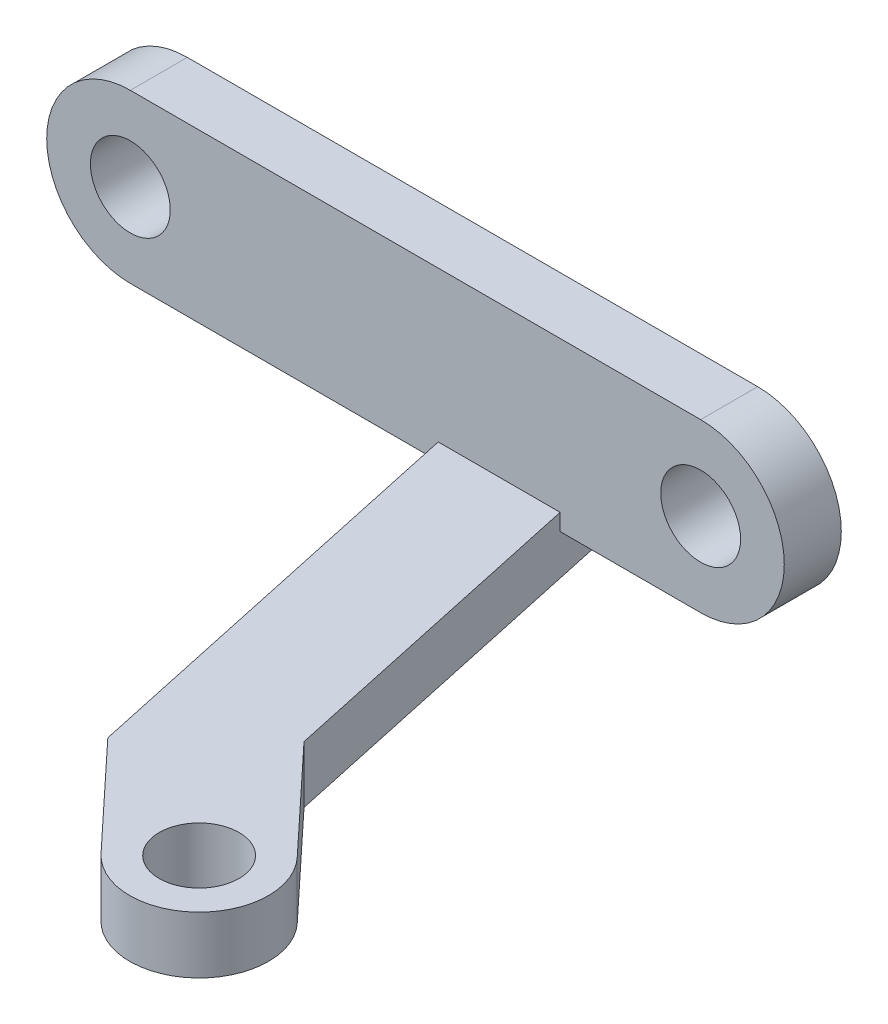
SolidWorks part; units mm, degrees
ref_plane "Front Plane" through (0, 0, 0) normal (0, 0, 1) x (1, 0, 0)
ref_plane "Top Plane" through (0, 0, 0) normal (0, 1, 0) x (1, 0, 0)
ref_plane "Right Plane" through (0, 0, 0) normal (1, 0, 0) x (0, 0, -1)
sketch "Sketch1" plane through (0, 0, 0) normal (0, 0, 1) x (1, 0, 0)
  line L0 (-51.4512, 4.712) -> (-76.4512, 4.712) construction
  line L1 (-51.4512, 1.0464) -> (-76.4512, 1.0464)
  line L2 (-51.4512, 8.3776) -> (-76.4512, 8.3776)
  circle A0 centre (-76.4512, 4.712) radius 1.75
  circle A1 centre (-51.4512, 4.712) radius 1.75
  arc A2 (-51.4512, 1.0464) -> (-51.4512, 8.3776) centre (-51.4512, 4.712) ccw
  arc A3 (-76.4512, 8.3776) -> (-76.4512, 1.0464) centre (-76.4512, 4.712) ccw
  point P6 (-63.9512, 4.712)
extrude "Boss-Extrude1" add sketch "Sketch1" along normal blind 2.5
sketch "Sketch2" plane through (0, 1.7778, 0) normal (0, -1, 0) x (1, 0, 0)
  line L1 (-41.8935, 5.019) -> (-95.3935, 55.019) construction
  line L6 (-54.5188, 16.8184) -> (-58.1496, 0)
  line L7 (-58.1496, 0) -> (-63.4924, 0)
  line L8 (-63.4924, 0) -> (-58.9646, 20.9733)
  line L9 (-58.9646, 20.9733) -> (-54.7175, 25.5177)
  line L11 (-50.2717, 21.3628) -> (-54.5188, 16.8184)
  line L12 (-50.2717, 21.3628) -> (-54.7175, 25.5177)
  arc A0 (-54.7175, 25.5177) -> (-50.2717, 21.3628) centre (-52.4946, 23.4403) cw
  circle A1 centre (-52.4946, 23.4403) radius 1.75
  line M12 (-95.3935, 55.019) -> (-41.8935, 5.019)
  dimension "D1" = 3.5
extrude "Boss-Extrude2" add sketch "Sketch2" along normal blind 2.5 contours A1 L12 A0 | A1 L12 L9 L11 M12 | L8 L7 L6 M12
